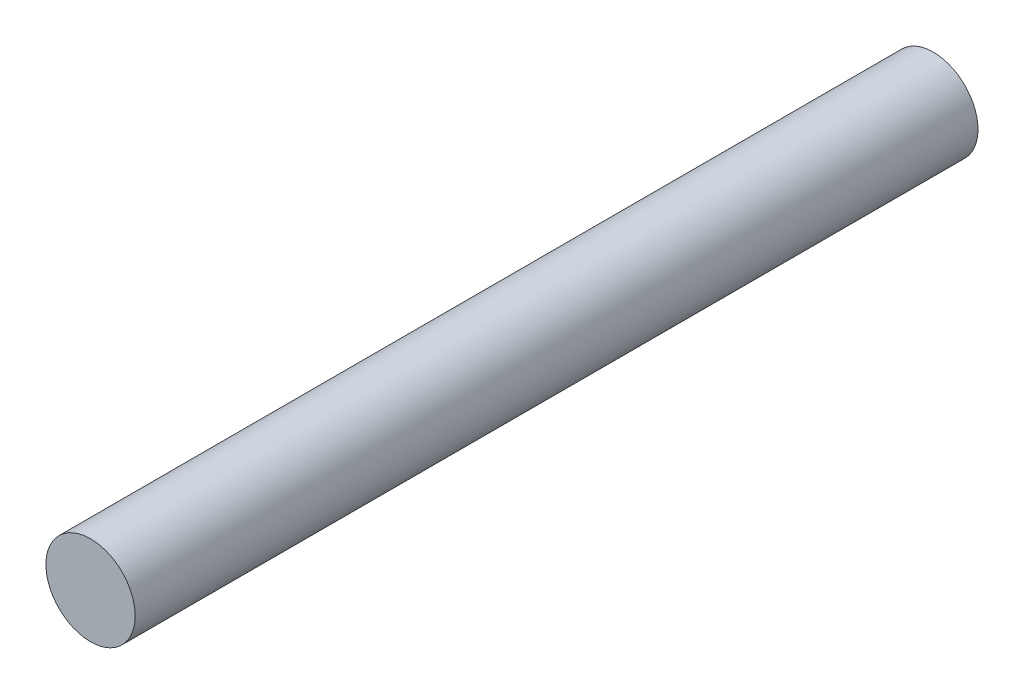
SolidWorks part; units mm, degrees
ref_plane "Front Plane" through (0, 0, 0) normal (0, 0, 1) x (1, 0, 0)
ref_plane "Top Plane" through (0, 0, 0) normal (0, 1, 0) x (1, 0, 0)
ref_plane "Right Plane" through (0, 0, 0) normal (1, 0, 0) x (0, 0, -1)
sketch "Sketch1" plane through (0, 0, 0) normal (0, 0, 1) x (1, 0, 0)
  circle A0 centre (0, 0) radius 4.7625
  dimension "D1" = 9.525
extrude "Boss-Extrude1" add sketch "Sketch1" along normal blind 89.9477
